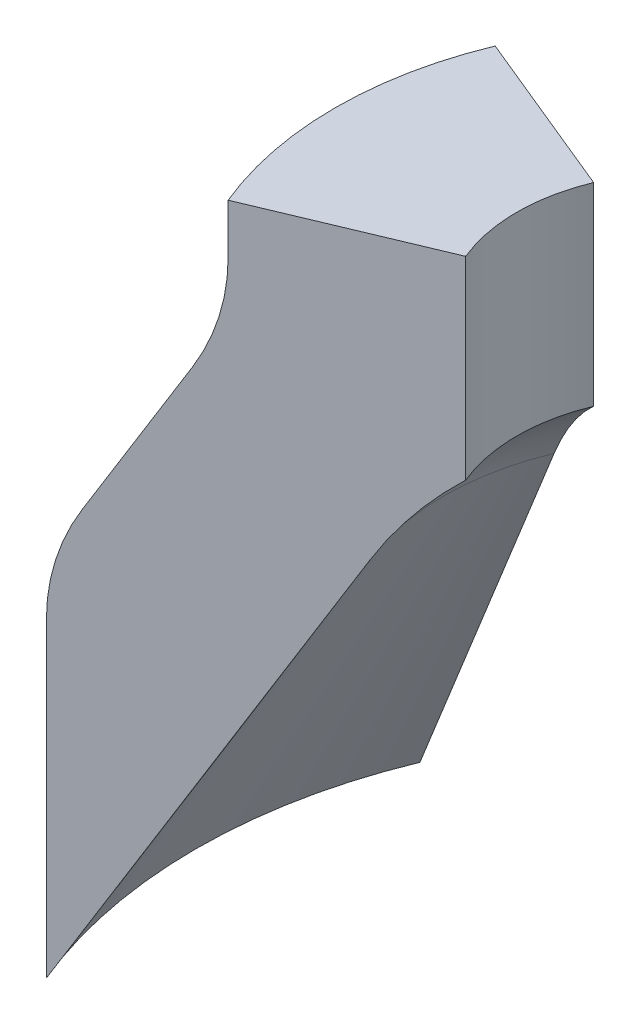
SolidWorks part; units mm, degrees
ref_plane "Front Plane" through (0, 0, 0) normal (0, 0, 1) x (1, 0, 0)
ref_plane "Top Plane" through (0, 0, 0) normal (0, 1, 0) x (1, 0, 0)
ref_plane "Right Plane" through (0, 0, 0) normal (1, 0, 0) x (0, 0, -1)
sketch "Sketch1" plane through (0, 0, 0) normal (0, 0, 1) x (1, 0, 0)
  line L2 (-26.24, -17.4475) -> (-26.24, -0.7311)
  line L5 (0, 0) -> (0, -20.833) construction
  line L8 (-24.7669, 4.7678) -> (-20.2342, 12.6207)
  line L9 (-18.7611, 18.1196) -> (-18.7611, 20.7939)
  line L10 (-18.7611, 20.7939) -> (-8.9838, 20.8251)
  line L12 (-26.24, -17.4475) -> (-12.9089, 5.6485)
  line L13 (-8.9838, 20.8251) -> (-8.9838, 10.4058)
  arc A2 (-24.7669, 4.7678) -> (-26.24, -0.7311) centre (-15.24, -0.7311) ccw
  arc A8 (-18.7611, 18.1196) -> (-20.2342, 12.6207) centre (-29.7611, 18.1196) cw
  arc A11 (-8.9838, 10.4058) -> (-12.9089, 5.6485) centre (3.2196, -3.6609) ccw
  point P1 (0, 0)
  dimension "D2" = 11
  dimension "D1" = 11
revolve "Revolve1" add sketch "Sketch1" angle 45 mid plane about L5
sketch "Sketch4" plane through (0, 0, 0) normal (0, 0, 1) x (1, 0, 0)
  line L19 (-18.069, 11.3709) -> (-22.6017, 3.518)
  line L20 (-16.2611, 18.3019) -> (-16.2611, 18.1196)
  line L21 (-11.4838, 18.3171) -> (-16.2611, 18.3019)
  line L22 (-11.4838, 11.5038) -> (-11.4838, 18.3171)
  line L23 (-23.74, -8.1153) -> (-15.0741, 6.8983)
  line L24 (-23.74, -0.7311) -> (-23.74, -8.1153)
  line L25 (-18.069, 11.3709) -> (-22.6017, 3.518)
  line L26 (-16.2611, 18.3019) -> (-16.2611, 18.1196)
  line L27 (-11.4838, 18.3171) -> (-16.2611, 18.3019)
  line L28 (-11.4838, 11.5038) -> (-11.4838, 18.3171)
  line L29 (-23.74, -8.1153) -> (-15.0741, 6.8983)
  line L30 (-23.74, -0.7311) -> (-23.74, -8.1153)
  arc A10 (-18.069, 11.3709) -> (-16.2611, 18.1196) centre (-29.7611, 18.1196) ccw
  arc A11 (-11.4838, 11.5038) -> (-15.0741, 6.8983) centre (3.2196, -3.6609) ccw
  arc A12 (-22.6017, 3.518) -> (-23.74, -0.7311) centre (-15.24, -0.7311) ccw
  arc A13 (-18.069, 11.3709) -> (-16.2611, 18.1196) centre (-29.7611, 18.1196) ccw
  arc A14 (-11.4838, 11.5038) -> (-15.0741, 6.8983) centre (3.2196, -3.6609) ccw
  arc A15 (-22.6017, 3.518) -> (-23.74, -0.7311) centre (-15.24, -0.7311) ccw
  dimension "D1" = 2.5
revolve "Cut-Revolve5" cut sketch "Sketch4" angle 23 mid plane about L5
ref_plane "Plane1" through (-0.0719, 20.8534, 0) normal (0.0034, -1, 0) x (-1, -0.0034, 0)
sketch "Sketch5" plane through (-0.0719, 20.8534, 0) normal (0.0034, -1, 0) x (-1, -0.0034, 0)
  circle A0 centre (13.8, 0) radius 2.5
extrude "Cut-Extrude1" cut sketch "Sketch5" along normal blind 2.55
